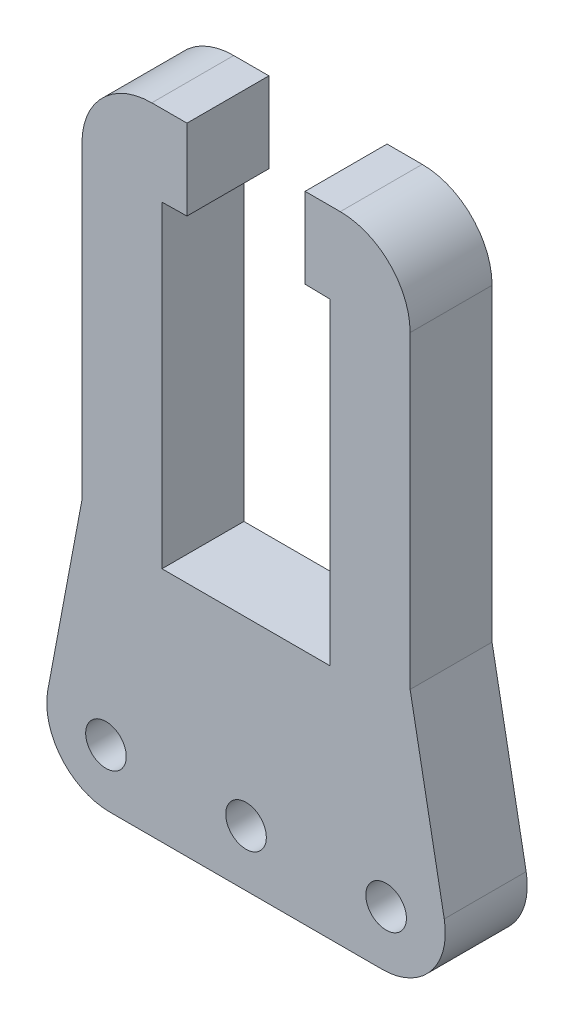
SolidWorks part; units mm, degrees
material "Acrylic (Medium-high impact)"
ref_plane "Front Plane" through (0, 0, 0) normal (0, 0, 1) x (1, 0, 0)
ref_plane "Top Plane" through (0, 0, 0) normal (0, 1, 0) x (1, 0, 0)
ref_plane "Right Plane" through (0, 0, 0) normal (1, 0, 0) x (0, 0, -1)
sketch "Model" plane through (0, 0, 0) normal (0, 0, 1) x (1, 0, 0)
  line L0 (519.9822, -457.799) -> (519.9822, 49542.201) construction
  line L1 (508.2671, 556.4886) -> (505.8314, 543.5174)
  line L2 (519.9822, 542.201) -> (509.9822, 542.201) construction
  line L3 (513.9822, 555.0932) -> (525.9822, 555.0932)
  line L4 (510.2558, 538.1848) -> (529.7087, 538.1848)
  line L5 (508.2671, 578.5517) -> (508.2671, 556.4886)
  line L6 (515.7654, 583.5381) -> (513.2535, 583.5381)
  line L7 (515.7654, 577.7922) -> (515.7654, 583.5381)
  line L8 (513.9822, 577.7627) -> (515.7654, 577.7922)
  line L9 (513.9822, 555.0932) -> (513.9822, 577.7627)
  line L10 (519.9822, 542.201) -> (529.9822, 542.201) construction
  line L80 (525.9822, 555.0932) -> (525.9822, 577.7627)
  line L81 (525.9822, 577.7627) -> (524.1991, 577.7922)
  line L82 (524.1991, 577.7922) -> (524.1991, 583.5381)
  line L83 (524.1991, 583.5381) -> (526.711, 583.5381)
  line L84 (531.6974, 578.5517) -> (531.6974, 556.4886)
  line L85 (531.6974, 556.4886) -> (534.1331, 543.5174)
  circle A0 centre (509.9822, 542.201) radius 1.45
  arc A1 (526.711, 583.5381) -> (531.6974, 578.5517) centre (526.711, 578.5517) cw
  arc A2 (505.8314, 543.5174) -> (510.2558, 538.1848) centre (510.2558, 542.6865) ccw
  arc A3 (534.1331, 543.5174) -> (529.7087, 538.1848) centre (529.7087, 542.6865) cw
  arc A4 (513.2535, 583.5381) -> (508.2671, 578.5517) centre (513.2535, 578.5517) ccw
  circle A5 centre (519.9822, 542.201) radius 1.45
  circle A6 centre (529.9822, 542.201) radius 1.45
  point P2 (519.9822, 555.0932)
  point P5 (519.9822, 538.1848)
  point P6 (519.9822, 555.0932)
  point P13 (519.9822, 538.1848)
  dimension "D1" = 12
  dimension "D2" = 22.6695
  dimension "D3" = 10
extrude "Boss-Extrude1" add sketch "Model" along normal blind 5.85
